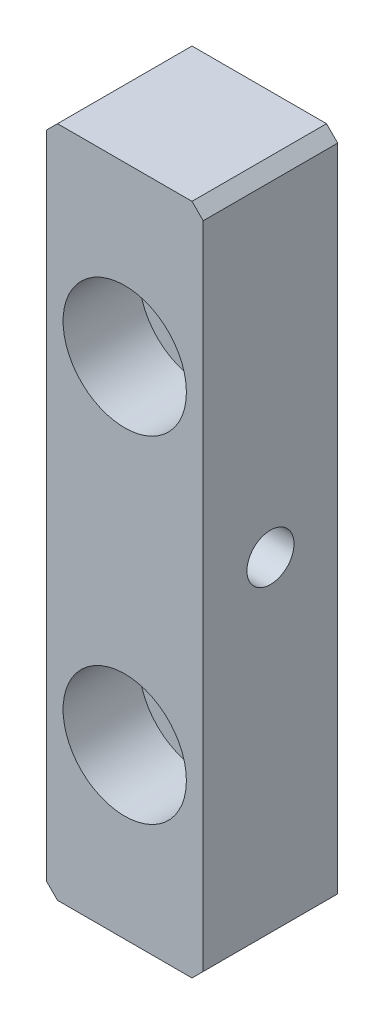
SolidWorks part; units mm, degrees
ref_plane "前视基准面" through (0, 0, 0) normal (0, 0, 1) x (1, 0, 0)
ref_plane "上视基准面" through (0, 0, 0) normal (0, 1, 0) x (1, 0, 0)
ref_plane "右视基准面" through (0, 0, 0) normal (1, 0, 0) x (0, 0, -1)
sketch "草图1" plane through (0, 0, 0) normal (0, 0, 1) x (1, 0, 0)
  line L1 (-7, -30) -> (7, -30)
  line L2 (-7, -30) -> (-7, 30)
  line L3 (-7, 30) -> (7, 30)
  line L4 (7, -30) -> (7, 30)
  line L5 (-7, -30) -> (7, 30) construction
  line L6 (-7, 30) -> (7, -30) construction
  point P0 (0, 0)
  dimension "D1" = 14
  dimension "D2" = 60
extrude "凸台-拉伸1" add sketch "草图1" along normal blind 12
sketch "草图2" plane through (0, 0, 12) normal (0, 0, 1) x (1, 0, 0)
  line L0 (7, 30) -> (-7, 30) construction
  point P0 (0, 15)
  dimension "D1" = 15
hole_wizard "M6 六角圆柱头螺钉的柱形沉头孔1" positions "草图2" profile "草图3" counterbore size "M6" standard "GB" end condition through all
sketch "草图3" plane through (0, 15, 12) normal (1, 0, 0) x (0, -1, 0)
  line L0 (0, 0) -> (0, 12)
  line L1 (0, 12) -> (3.3, 12)
  line L3 (3.3, 12) -> (3.3, 6.8)
  line L4 (3.3, 6.8) -> (5.5, 6.8)
  line L5 (5.5, 6.8) -> (5.5, 0)
  line L7 (5.5, 0) -> (0, 0)
  line L11 (0, -6.35) -> (0, 107.95) construction
  dimension "通孔孔直径" = 6.6
  dimension "通孔孔深度" = 12
  dimension "柱形沉头孔直径" = 11
  dimension "柱形沉头孔深度" = 6.8
mirror "镜向1" about plane through (0, 0, 0) normal (0, 1, 0) of "M6 六角圆柱头螺钉的柱形沉头孔1"
chamfer "倒角1" distance 1 angle 45 4 edges at (7, -30, 6) (-7, -30, 6) (-7, 30, 6) (7, 30, 6)
sketch "草图4" plane through (7, 0, 0) normal (1, 0, 0) x (0, 0, -1)
  line L0 (0, 0) -> (-12, 0) construction
  line L1 (-12, -29) -> (-12, 29) construction
  point P5 (-6, 0)
hole_wizard "M5 螺纹孔1" positions "草图4" profile "草图5" tap size "M5" standard "GB" end condition through all
sketch "草图5" plane through (7, 0, 6) normal (0, 1, 0) x (0, 0, -1)
  line L0 (0, 0) -> (0, 14)
  line L1 (0, 14) -> (2.1, 14)
  line L2 (2.1, 14) -> (2.1, 0)
  line L5 (2.1, 0) -> (0, 0)
  line L11 (0, -6.35) -> (0, 107.95) construction
  dimension "通孔螺纹孔钻头直径" = 4.2
  dimension "通孔螺纹孔钻头深度" = 14
cosmetic thread "孔螺纹线1" parameters "D2"=5
